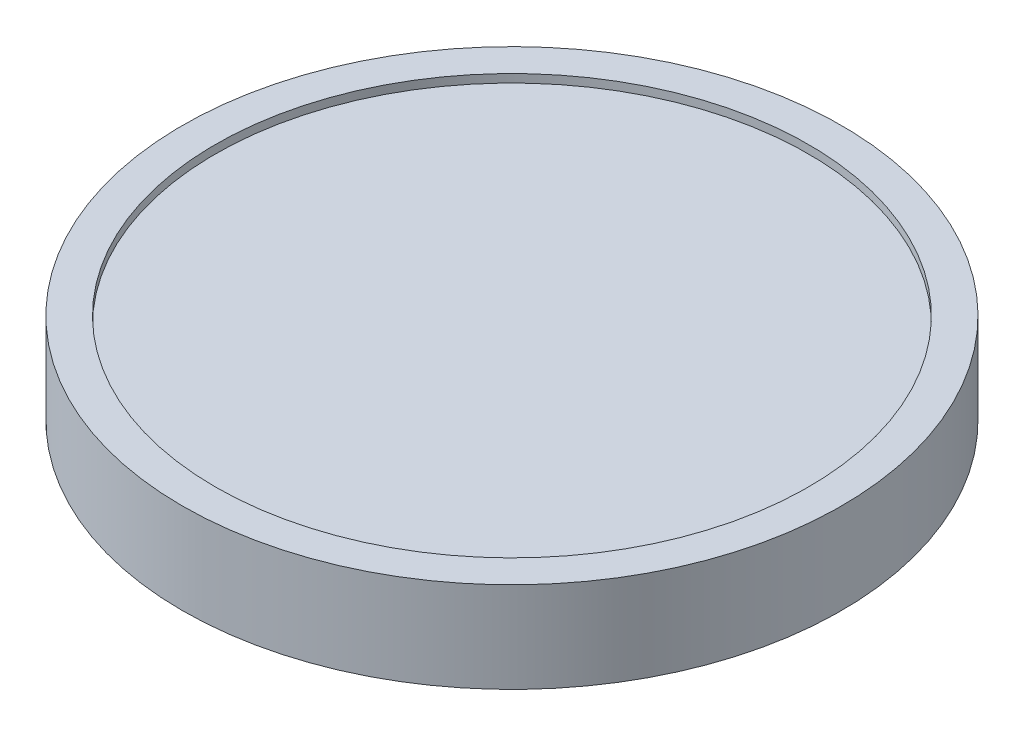
SolidWorks part; units mm, degrees
ref_plane "Ön Düzlem" through (0, 0, 0) normal (0, 0, 1) x (1, 0, 0)
ref_plane "Üst Düzlem" through (0, 0, 0) normal (0, 1, 0) x (1, 0, 0)
ref_plane "Sağ Düzlem" through (0, 0, 0) normal (1, 0, 0) x (0, 0, -1)
sketch "Çizim1" plane through (0, 0, 0) normal (0, 1, 0) x (1, 0, 0)
  circle A0 centre (-6.9821, 12.9244) radius 40
  dimension "D1" = 80
extrude "Yükseklik-Ekstrüzyon1" add sketch "Çizim1" along normal blind 11
sketch "Çizim2" plane through (0, 11, 0) normal (0, 1, 0) x (1, 0, 0)
  line L0 (-6.9821, 52.9244) -> (-6.9821, -27.0756) construction
  circle A0 centre (-6.9821, 12.9244) radius 40 construction
  circle A1 centre (-6.9821, 12.9244) radius 36
  dimension "D1" = 72
extrude "Kes-Ekstrüzyon2" cut sketch "Çizim2" against normal blind 1
sketch "Çizim3" plane through (0, 0, 0) normal (0, -1, 0) x (1, 0, 0)
  line L0 (-6.9821, -52.9244) -> (-6.9821, 27.0756) construction
  line L2 (-0.4821, -20.9244) -> (-13.4821, -20.9244)
  line L3 (-0.4821, -20.9244) -> (-0.4821, -4.9244)
  line L4 (-0.4821, -4.9244) -> (-13.4821, -4.9244)
  line L5 (-13.4821, -20.9244) -> (-13.4821, -4.9244)
  line L6 (-0.4821, -20.9244) -> (-13.4821, -4.9244) construction
  line L7 (-0.4821, -4.9244) -> (-13.4821, -20.9244) construction
  circle A0 centre (-6.9821, -12.9244) radius 40 construction
  point P5 (-6.9821, -12.9244)
  dimension "D1" = 13
  dimension "D2" = 16
extrude "Yükseklik-Ekstrüzyon2" add sketch "Çizim3" along normal blind 7
